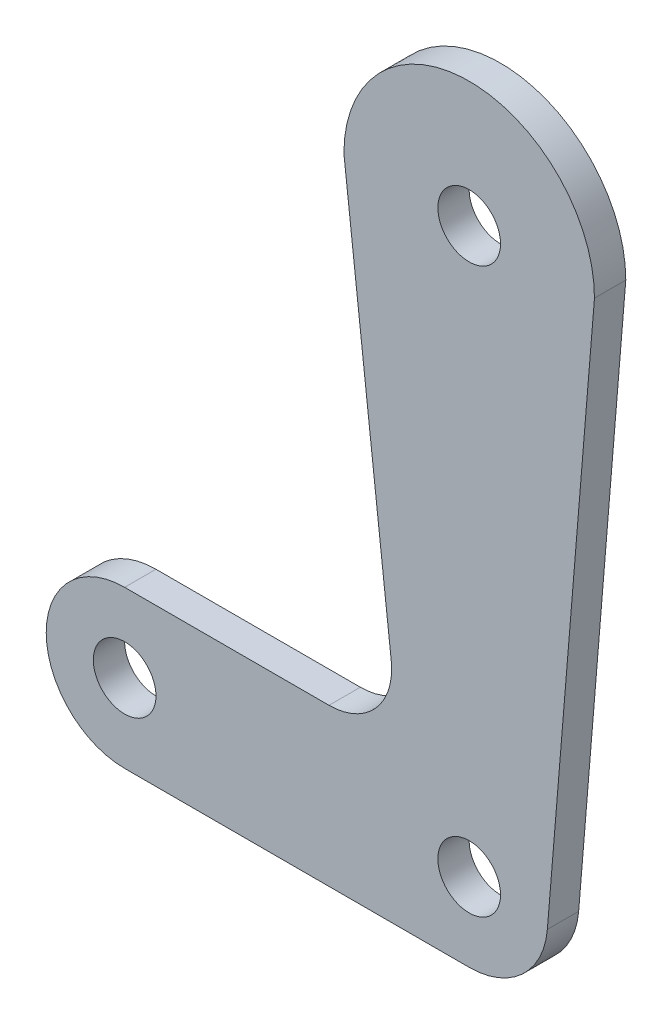
SolidWorks part; units mm, degrees
ref_plane "Front Plane" through (0, 0, 0) normal (0, 0, 1) x (1, 0, 0)
ref_plane "Top Plane" through (0, 0, 0) normal (0, 1, 0) x (1, 0, 0)
ref_plane "Right Plane" through (0, 0, 0) normal (1, 0, 0) x (0, 0, -1)
sketch "Sketch1" plane through (0, 0, 0) normal (0, 0, 1) x (1, 0, 0)
  line L0 (0, 0) -> (-4894.3614, 0) construction
  line L1 (0, 0) -> (34.925, 0) construction
  line L2 (0, 7.9502) -> (20.716, 7.9502)
  line L3 (0, -7.9502) -> (34.925, -7.9502)
  line L4 (34.925, 0) -> (34.925, 50000) construction
  line L5 (22.225, 57.15) -> (27.0252, 15.019)
  line L6 (47.625, 57.15) -> (42.8482, -0.6547)
  arc A0 (0, 7.9502) -> (0, -7.9502) centre (0, 0) ccw
  arc A1 (34.925, -7.9502) -> (42.8752, 0) centre (34.925, 0) ccw
  circle A2 centre (0, 0) radius 3.175
  circle A3 centre (34.925, 0) radius 3.175
  circle A4 centre (34.925, 57.15) radius 3.175
  arc A5 (47.4527, 55.0653) -> (22.5505, 54.2931) centre (34.925, 57.15) ccw
  arc A6 (27.0252, 15.019) -> (20.716, 7.9502) centre (20.716, 14.3002) cw
  point P5 (0, 7.5777)
  point P25 (17.3215, 0)
  point P26 (0, 0)
  point P27 (0, 0)
  dimension "D2" = 7.9502
  dimension "D3" = 6.35
  dimension "D4" = 6.35
  dimension "D5" = 6.35
  dimension "D6" = 25.4
  dimension "D8" = 6.35
  dimension "D1" = 34.925
  dimension "D7" = 57.15
  dimension "D9" = 6.5
extrude "Boss-Extrude1" add sketch "Sketch1" along normal blind 3.175
